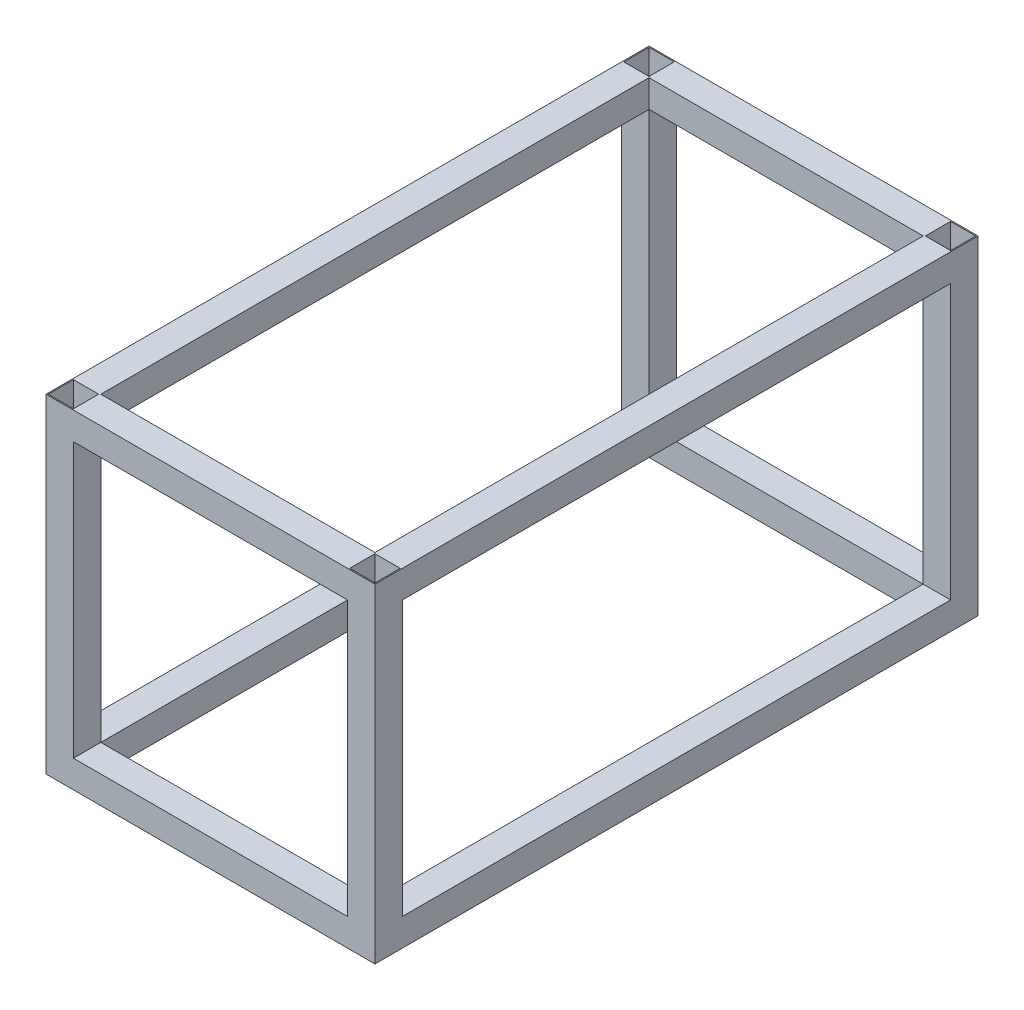
SolidWorks part; units mm, degrees
material "1023 Carbon Steel Sheet (SS)"
ref_plane "Front Plane" through (0, 0, 0) normal (0, 0, 1) x (1, 0, 0)
ref_plane "Top Plane" through (0, 0, 0) normal (0, 1, 0) x (1, 0, 0)
ref_plane "Right Plane" through (0, 0, 0) normal (1, 0, 0) x (0, 0, -1)
sketch "Sketch1" plane through (0, 0, 0) normal (0, 1, 0) x (1, 0, 0)
  line L0 (-128, 255) -> (-151.4, 255)
  line L1 (-127, 254) -> (127, 254) construction
  line L2 (-127, 254) -> (-127, -254) construction
  line L3 (-127, -254) -> (127, -254) construction
  line L4 (127, 254) -> (127, -254) construction
  line L5 (-127, 254) -> (127, -254) construction
  line L6 (-127, -254) -> (127, 254) construction
  line L7 (127, 254) -> (152.4, 254)
  line L8 (127, 254) -> (127, 279.4)
  line L9 (127, 279.4) -> (152.4, 279.4)
  line L10 (152.4, 254) -> (152.4, 279.4)
  line L11 (127, -254) -> (152.4, -254)
  line L12 (127, -254) -> (127, -279.4)
  line L13 (127, -279.4) -> (152.4, -279.4)
  line L14 (152.4, -254) -> (152.4, -279.4)
  line L15 (-127, -254) -> (-152.4, -254)
  line L16 (-127, -254) -> (-127, -279.4)
  line L17 (-127, -279.4) -> (-152.4, -279.4)
  line L18 (-152.4, -254) -> (-152.4, -279.4)
  line L19 (-127, 254) -> (-152.4, 254)
  line L20 (-127, 254) -> (-127, 279.4)
  line L21 (-127, 279.4) -> (-152.4, 279.4)
  line L22 (-152.4, 254) -> (-152.4, 279.4)
  line L23 (-151.4, 255) -> (-151.4, 278.4)
  line L24 (-128, 278.4) -> (-151.4, 278.4)
  line L25 (-128, 255) -> (-128, 278.4)
  line L26 (128, 255) -> (151.4, 255)
  line L27 (151.4, 255) -> (151.4, 278.4)
  line L28 (128, 278.4) -> (151.4, 278.4)
  line L29 (128, 255) -> (128, 278.4)
  line L30 (-128, -255) -> (-151.4, -255)
  line L31 (-151.4, -255) -> (-151.4, -278.4)
  line L32 (-128, -278.4) -> (-151.4, -278.4)
  line L33 (-128, -255) -> (-128, -278.4)
  line L34 (128, -255) -> (151.4, -255)
  line L35 (151.4, -255) -> (151.4, -278.4)
  line L36 (128, -278.4) -> (151.4, -278.4)
  line L37 (128, -255) -> (128, -278.4)
  point P0 (0, 0)
  dimension "D1" = 254
  dimension "D2" = 508
  dimension "D3" = 25.4
  dimension "D4" = 25.4
  dimension "D5" = 25.4
  dimension "D6" = 25.4
  dimension "D7" = 25.4
  dimension "D8" = 25.4
  dimension "D9" = 25.4
  dimension "D10" = 25.4
  dimension "D11" = 1
  dimension "D12" = 1
extrude "Boss-Extrude1" add sketch "Sketch1" along normal blind 304.8 contours L15 L18 L17 L16 | L11 L14 L13 L12 | L7 L10 L9 L8 | L19 L22 L21 L20 | L30 L31 L32 L33 | L34 L35 L36 L37 | L26 L27 L28 L29 | L0 L23 L24 L25
sketch "Sketch2" plane through (0, 0, -254) normal (0, 0, 1) x (1, 0, 0)
  line L0 (152.4, 304.8) -> (152.4, 0) construction
  line L1 (127, 304.8) -> (152.4, 304.8)
  line L2 (127, 304.8) -> (127, 279.4)
  line L3 (127, 279.4) -> (152.4, 279.4)
  line L4 (152.4, 304.8) -> (152.4, 279.4)
  line L5 (128, 280.4) -> (151.4, 280.4)
  line L6 (151.4, 303.8) -> (151.4, 280.4)
  line L7 (128, 303.8) -> (151.4, 303.8)
  line L8 (128, 303.8) -> (128, 280.4)
  line L9 (127, 25.4) -> (152.4, 25.4)
  line L10 (127, 25.4) -> (127, 0)
  line L11 (127, 0) -> (152.4, 0)
  line L12 (152.4, 25.4) -> (152.4, 0)
  line L13 (128, 1) -> (151.4, 1)
  line L14 (151.4, 24.4) -> (151.4, 1)
  line L15 (128, 24.4) -> (151.4, 24.4)
  line L16 (128, 24.4) -> (128, 1)
  line L17 (127, 0) -> (152.4, 0) construction
  dimension "D1" = 25.4
  dimension "D3" = 23.4
  dimension "D4" = 25.4
  dimension "D5" = 25.4
  dimension "D6" = 1
  dimension "D7" = 1
  dimension "D8" = 1
  dimension "D9" = 23.4
  dimension "D2" = 1
extrude "Boss-Extrude2" add sketch "Sketch2" along normal up to next (508 mm away)
sketch "Sketch3" plane through (127, 0, 0) normal (-1, 0, 0) x (0, 0, 1)
  line L0 (-255, 280.4) -> (-278.4, 280.4)
  line L1 (279.4, 304.8) -> (254, 304.8)
  line L2 (279.4, 304.8) -> (279.4, 279.4)
  line L3 (279.4, 279.4) -> (254, 279.4)
  line L4 (254, 304.8) -> (254, 279.4)
  line L5 (-254, 279.4) -> (-279.4, 279.4)
  line L6 (-254, 279.4) -> (-254, 304.8)
  line L7 (-254, 304.8) -> (-279.4, 304.8)
  line L8 (-279.4, 279.4) -> (-279.4, 304.8)
  line L9 (279.4, 0) -> (254, 0)
  line L10 (279.4, 0) -> (279.4, 25.4)
  line L11 (279.4, 25.4) -> (254, 25.4)
  line L12 (254, 0) -> (254, 25.4)
  line L13 (-254, 25.4) -> (-279.4, 25.4)
  line L14 (-254, 25.4) -> (-254, 0)
  line L15 (-254, 0) -> (-279.4, 0)
  line L16 (-279.4, 25.4) -> (-279.4, 0)
  line L17 (-278.4, 280.4) -> (-278.4, 303.8)
  line L18 (-255, 303.8) -> (-278.4, 303.8)
  line L19 (-255, 280.4) -> (-255, 303.8)
  line L20 (-255, 24.4) -> (-278.4, 24.4)
  line L21 (-278.4, 24.4) -> (-278.4, 1)
  line L22 (-255, 1) -> (-278.4, 1)
  line L23 (-255, 24.4) -> (-255, 1)
  line L24 (278.4, 303.8) -> (255, 303.8)
  line L25 (255, 303.8) -> (255, 280.4)
  line L26 (278.4, 280.4) -> (255, 280.4)
  line L27 (278.4, 303.8) -> (278.4, 280.4)
  line L28 (278.4, 1) -> (255, 1)
  line L29 (255, 1) -> (255, 24.4)
  line L30 (278.4, 24.4) -> (255, 24.4)
  line L31 (278.4, 1) -> (278.4, 24.4)
  dimension "D1" = 1
extrude "Boss-Extrude4" add sketch "Sketch3" along normal up to next
pattern_linear "LPattern2" count 2 spacing 279.4 along (-1, 0, 0) of "Boss-Extrude2"
